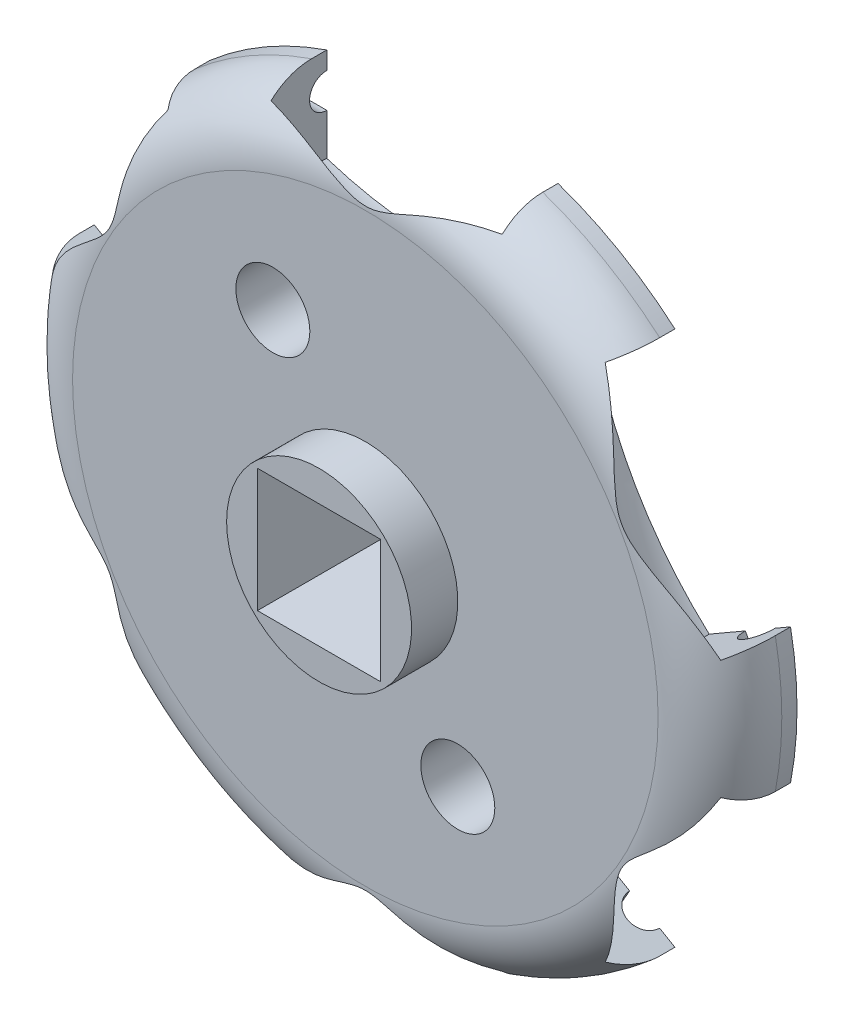
SolidWorks part; units mm, degrees
ref_plane "Front Plane" through (0, 0, 0) normal (0, 0, 1) x (1, 0, 0)
ref_plane "Top Plane" through (0, 0, 0) normal (0, 1, 0) x (1, 0, 0)
ref_plane "Right Plane" through (0, 0, 0) normal (1, 0, 0) x (0, 0, -1)
sketch "Sketch1" plane through (0, 0, 0) normal (0, 0, 1) x (1, 0, 0)
  circle A0 centre (0, 0) radius 18.2626
  dimension "D1" = 36.5252
extrude "Boss-Extrude1" add sketch "Sketch1" along normal blind 3.9688
fillet "Fillet1" radius 3.1852 1 edges at (18.2626, 0, 3.9688)
sketch "Sketch2" plane through (0, 0, 3.9688) normal (0, 0, 1) x (1, 0, 0)
  line L0 (0, 0) -> (-9.0824, 15.7311) construction
  line L1 (0, 0) -> (0, 7.1566) construction
  line L3 (-3.175, -3.175) -> (3.175, -3.175)
  line L4 (-3.175, -3.175) -> (-3.175, 3.175)
  line L5 (-3.175, 3.175) -> (3.175, 3.175)
  line L6 (3.175, -3.175) -> (3.175, 3.175)
  line L7 (-3.175, -3.175) -> (3.175, 3.175) construction
  line L8 (-3.175, 3.175) -> (3.175, -3.175) construction
  circle A0 centre (-4.7625, 8.2489) radius 1.905
  circle A1 centre (4.7625, -8.2489) radius 1.905
  circle A4 centre (0, 0) radius 18.1647 construction
  point P7 (0.7694, -9.4939)
  point P9 (0, 0)
  point P17 (0, 7.1566)
  dimension "D2" = 3.81
  dimension "D4" = 6.35
  dimension "D1" = 9.525
  dimension "D5" = 30
  dimension "D6" = 6.35
  dimension "D3" = 2
extrude "Cut-Extrude1" cut sketch "Sketch2" against normal through all
sketch "Sketch5" plane through (0, 0, 0) normal (0, 0, 1) x (1, 0, 0)
  line L0 (-5.9531, 15.4623) -> (5.9531, 15.4623)
  line L1 (5.9531, 15.4623) -> (5.9531, 18.4966)
  line L2 (-5.9531, 15.4623) -> (-5.9531, 18.4966)
  line L3 (-5.9531, 15.4623) -> (-8.5086, 15.4623) construction
  arc A0 (-5.9531, 18.4966) -> (5.9531, 18.4966) centre (0, 0) cw
  circle A1 centre (0, 0) radius 18.1647 construction
  point P5 (0, 15.4623)
  point P9 (0, 19.431)
  dimension "D1" = 11.9062
  dimension "D2" = 15.4623
  dimension "D3" = 7.9375
revolve "Cut-Revolve1" cut sketch "Sketch5" angle 360 about L3
sketch "Sketch6" plane through (0, 0, 0) normal (1, 0, 0) x (0, 0, -1)
  line L0 (0, -17.1615) -> (0, 18.1647) construction
  circle A0 centre (0, 15.4623) radius 0.889
  arc A1 (-2.8739, 16.4358) -> (0, 12.4279) centre (0, 15.4623) ccw construction
  dimension "D1" = 1.778
extrude "Cut-Extrude2" cut sketch "Sketch6" against normal mid plane 15.875
pattern_circular "CirPattern1" count 6 over 360 about axis through (0, 0, 0) along (0, 0, 1) of "Cut-Revolve1", "Cut-Extrude2"
sketch "Sketch7" plane through (0, 0, 3.9688) normal (0, 0, 1) x (1, 0, 0)
  line L5 (3.175, -3.175) -> (3.175, 3.175)
  line L6 (-3.175, -3.175) -> (3.175, -3.175)
  line L7 (-3.175, 3.175) -> (-3.175, -3.175)
  line L8 (3.175, 3.175) -> (-3.175, 3.175)
  line L9 (3.175, -3.175) -> (3.175, 3.175)
  line L10 (-3.175, -3.175) -> (3.175, -3.175)
  line L11 (-3.175, 3.175) -> (-3.175, -3.175)
  line L12 (3.175, 3.175) -> (-3.175, 3.175)
  circle A0 centre (0, 0) radius 4.7625
  dimension "D2" = 9.525
  dimension "D1" = 0
extrude "Boss-Extrude2" add sketch "Sketch7" along normal blind 2.3813
